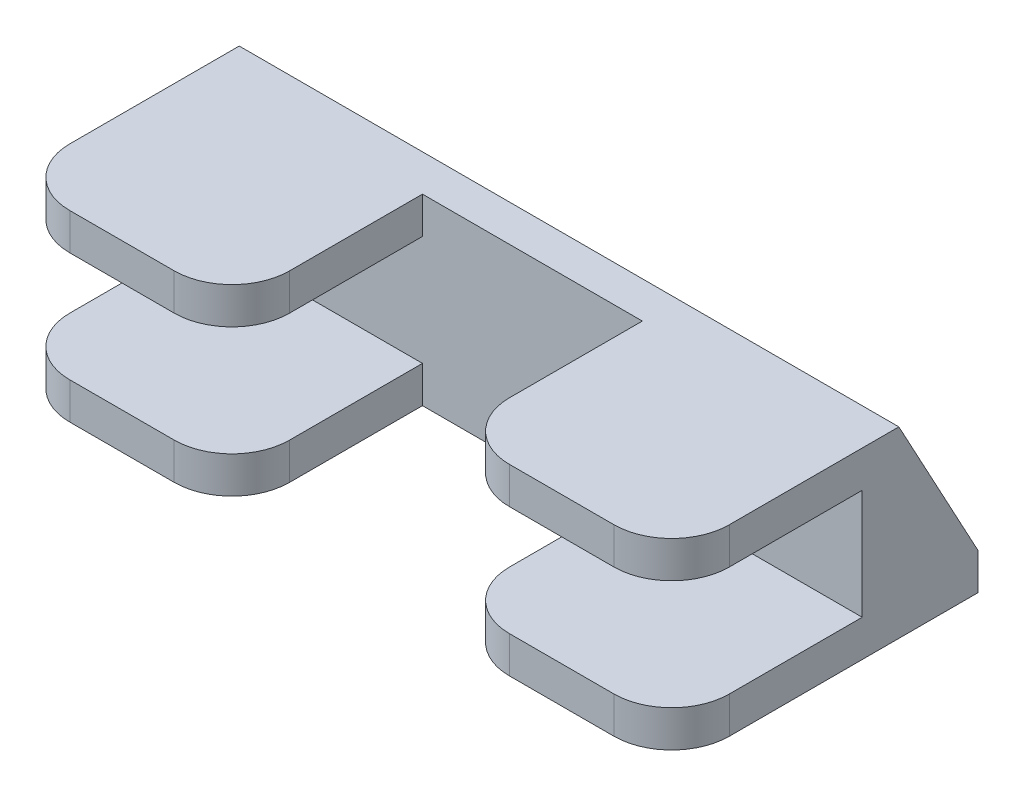
SolidWorks part; units mm, degrees
ref_plane "Front Plane" through (0, 0, 0) normal (0, 0, 1) x (1, 0, 0)
ref_plane "Top Plane" through (0, 0, 0) normal (0, 1, 0) x (1, 0, 0)
ref_plane "Right Plane" through (0, 0, 0) normal (1, 0, 0) x (0, 0, -1)
sketch "Sketch1" plane through (0, 0, 0) normal (0, 0, 1) x (1, 0, 0)
  line L1 (-57.15, -9.525) -> (57.15, -9.525)
  line L2 (-57.15, -9.525) -> (-57.15, 9.525)
  line L3 (-57.15, 9.525) -> (57.15, 9.525)
  line L4 (57.15, -9.525) -> (57.15, 9.525)
  line L5 (-57.15, -9.525) -> (57.15, 9.525) construction
  line L6 (-57.15, 9.525) -> (57.15, -9.525) construction
  point P0 (0, 0)
  dimension "D1" = 114.3
  dimension "D2" = 19.05
extrude "Boss-Extrude1" add sketch "Sketch1" along normal blind 6.35
sketch "Sketch3" plane through (0, -9.525, 0) normal (0, -1, 0) x (-1, 0, 0)
  line L0 (0, 0) -> (0, -50000) construction
  line L1 (57.15, 0) -> (-57.15, 0) construction
  line L2 (-57.15, -6.35) -> (-57.15, 0) construction
  line L3 (57.15, -39.37) -> (-57.15, -39.37)
  line L4 (57.15, -39.37) -> (57.15, 13.716)
  line L5 (57.15, 13.716) -> (-57.15, 13.716)
  line L6 (-57.15, -39.37) -> (-57.15, 13.716)
  line L7 (57.15, -39.37) -> (-57.15, 13.716) construction
  line L8 (57.15, 13.716) -> (-57.15, -39.37) construction
  line L9 (57.15, -6.35) -> (-57.15, -6.35) construction
  line L11 (19.05, -39.37) -> (-19.05, -39.37)
  line L12 (19.05, -39.37) -> (19.05, -6.35)
  line L13 (19.05, -6.35) -> (-19.05, -6.35)
  line L14 (-19.05, -39.37) -> (-19.05, -6.35)
  line L15 (19.05, -39.37) -> (-19.05, -6.35) construction
  line L16 (19.05, -6.35) -> (-19.05, -39.37) construction
  point P4 (0, 0)
  point P5 (0, -12.827)
  point P14 (0, -22.86)
  line M9 (57.15, 0) -> (-57.15, 0)
  line M10 (-57.15, 0) -> (-57.15, -6.35)
  line M11 (-57.15, -6.35) -> (57.15, -6.35)
  line M12 (57.15, -6.35) -> (57.15, 0)
  dimension "D1" = 20.066
  dimension "D2" = 33.02
  dimension "D3" = 38.1
extrude "Boss-Extrude2" add sketch "Sketch3" along normal blind 6.35 contours L12 L3 L4 M11 | L6 L4 L5 M9 | M12 M9 M10 M11 | L3 L14 L6 M11
sketch "Sketch4" plane through (0, 9.525, 0) normal (0, 1, 0) x (1, 0, 0)
  line L0 (57.15, -6.35) -> (19.05, -6.35) construction
  line L1 (19.05, -6.35) -> (19.05, -39.37) construction
  line L2 (19.05, -39.37) -> (57.15, -39.37) construction
  line L3 (57.15, -39.37) -> (57.15, -6.35) construction
  line L4 (57.15, 0) -> (-57.15, 0)
  line L5 (-57.15, 0) -> (-57.15, -6.35)
  line L6 (-57.15, -6.35) -> (57.15, -6.35)
  line L7 (57.15, -6.35) -> (57.15, 0)
  line L8 (57.15, 0) -> (-57.15, 0)
  line L9 (-57.15, 0) -> (-57.15, -6.35)
  line L10 (-57.15, -6.35) -> (57.15, -6.35)
  line L11 (57.15, -6.35) -> (57.15, 0)
  line L12 (-19.05, -6.35) -> (-57.15, -6.35) construction
  line L13 (-57.15, -6.35) -> (-57.15, -39.37) construction
  line L14 (-57.15, -39.37) -> (-19.05, -39.37) construction
  line L15 (-19.05, -39.37) -> (-19.05, -6.35) construction
  line L16 (57.15, -6.35) -> (19.05, -6.35)
  line L17 (19.05, -6.35) -> (19.05, -39.37)
  line L18 (19.05, -39.37) -> (57.15, -39.37)
  line L19 (57.15, -39.37) -> (57.15, -6.35)
  line L20 (-19.05, -6.35) -> (-57.15, -6.35)
  line L21 (-57.15, -6.35) -> (-57.15, -39.37)
  line L22 (-57.15, -39.37) -> (-19.05, -39.37)
  line L23 (-19.05, -39.37) -> (-19.05, -6.35)
  line M5 (57.15, 0) -> (-57.15, 0)
  line M6 (-57.15, 0) -> (-57.15, -6.35)
  line M7 (-57.15, -6.35) -> (57.15, -6.35)
  line M8 (57.15, -6.35) -> (57.15, 0)
  dimension "D1" = 0
extrude "Boss-Extrude3" add sketch "Sketch4" along normal blind 6.35 contours L18 L19 L10 L17 | L10 M8 M5 M6 M7 | L22 L23 L21 M7
sketch "Sketch6" plane through (0, -9.525, 0) normal (0, 1, 0) x (1, 0, 0)
  line L0 (-57.15, 0) -> (57.15, 0) construction
  line L1 (19.05, 13.716) -> (-19.05, 13.716)
  line L2 (19.05, 13.716) -> (19.05, 0)
  line L3 (19.05, 0) -> (-19.05, 0)
  line L4 (-19.05, 13.716) -> (-19.05, 0)
  line L5 (19.05, 13.716) -> (-19.05, 0) construction
  line L6 (19.05, 0) -> (-19.05, 13.716) construction
  line L7 (-57.15, 13.716) -> (57.15, 13.716) construction
  line L8 (-19.05, -39.37) -> (-19.05, -6.35) construction
  line L9 (19.05, -39.37) -> (19.05, -6.35) construction
  point P0 (0, 6.858)
extrude "Cut-Extrude1" cut sketch "Sketch6" against normal through all
sketch "Sketch5" plane through (57.15, 0, 0) normal (1, 0, 0) x (0, 0, -1)
  line L0 (13.716, -9.525) -> (0, 15.875)
  line L1 (0, 15.875) -> (0, -9.525)
  line L2 (0, -9.525) -> (13.716, -9.525)
extrude "Boss-Extrude4" add sketch "Sketch5" against normal blind 6.35
sketch "Sketch7" plane through (19.05, 0, 0) normal (-1, 0, 0) x (0, 0, 1)
  line L3 (-13.716, -9.525) -> (0, -9.525)
  line L4 (0, -9.525) -> (0, 15.875)
  line L5 (0, 15.875) -> (-13.716, -9.525)
  line L6 (-13.716, -9.525) -> (0, -9.525)
  line L7 (0, -9.525) -> (0, 15.875)
  line L8 (0, 15.875) -> (-13.716, -9.525)
  dimension "D1" = 0
extrude "Boss-Extrude5" add sketch "Sketch7" against normal blind 6.35
sketch "Sketch8" plane through (-19.05, 0, 0) normal (1, 0, 0) x (0, 0, -1)
  line L3 (13.716, -9.525) -> (0, 15.875)
  line L4 (0, 15.875) -> (0, -9.525)
  line L5 (0, -9.525) -> (13.716, -9.525)
  line L6 (13.716, -9.525) -> (0, 15.875)
  line L7 (0, 15.875) -> (0, -9.525)
  line L8 (0, -9.525) -> (13.716, -9.525)
  dimension "D1" = 0
extrude "Boss-Extrude6" add sketch "Sketch8" against normal blind 6.35
sketch "Sketch9" plane through (-57.15, 0, 0) normal (-1, 0, 0) x (0, 0, 1)
  line L3 (-13.716, -9.525) -> (0, -9.525)
  line L4 (0, -9.525) -> (0, 15.875)
  line L5 (0, 15.875) -> (-13.716, -9.525)
  line L6 (-13.716, -9.525) -> (0, -9.525)
  line L7 (0, -9.525) -> (0, 15.875)
  line L8 (0, 15.875) -> (-13.716, -9.525)
  dimension "D1" = 0
extrude "Boss-Extrude7" add sketch "Sketch9" against normal blind 6.35
sketch "Sketch10" plane through (0, -9.525, 0) normal (0, 1, 0) x (1, 0, 0)
  line L0 (38.1, 0) -> (38.1, 13.716) construction
  line L1 (25.4, 0) -> (50.8, 0) construction
  line L2 (25.4, 13.716) -> (50.8, 13.716) construction
  line L3 (-38.1, 0) -> (-38.1, 13.716) construction
  line L4 (-50.8, 0) -> (-25.4, 0) construction
  line L5 (-50.8, 13.716) -> (-25.4, 13.716) construction
  circle A0 centre (38.1, 6.858) radius 2.286
  circle A1 centre (-38.1, 6.858) radius 2.286
  dimension "D1" = 4.572
extrude "Cut-Extrude2" cut sketch "Sketch10" against normal through all
fillet "Fillet2" radius 10 8 edges at (-57.15, 12.7, 39.37) (-57.15, -12.7, 39.37) (-19.05, -12.7, 39.37) (19.05, -12.7, 39.37) (57.15, -12.7, 39.37) (-19.05, 12.7, 39.37) (19.05, 12.7, 39.37) (57.15, 12.7, 39.37)
